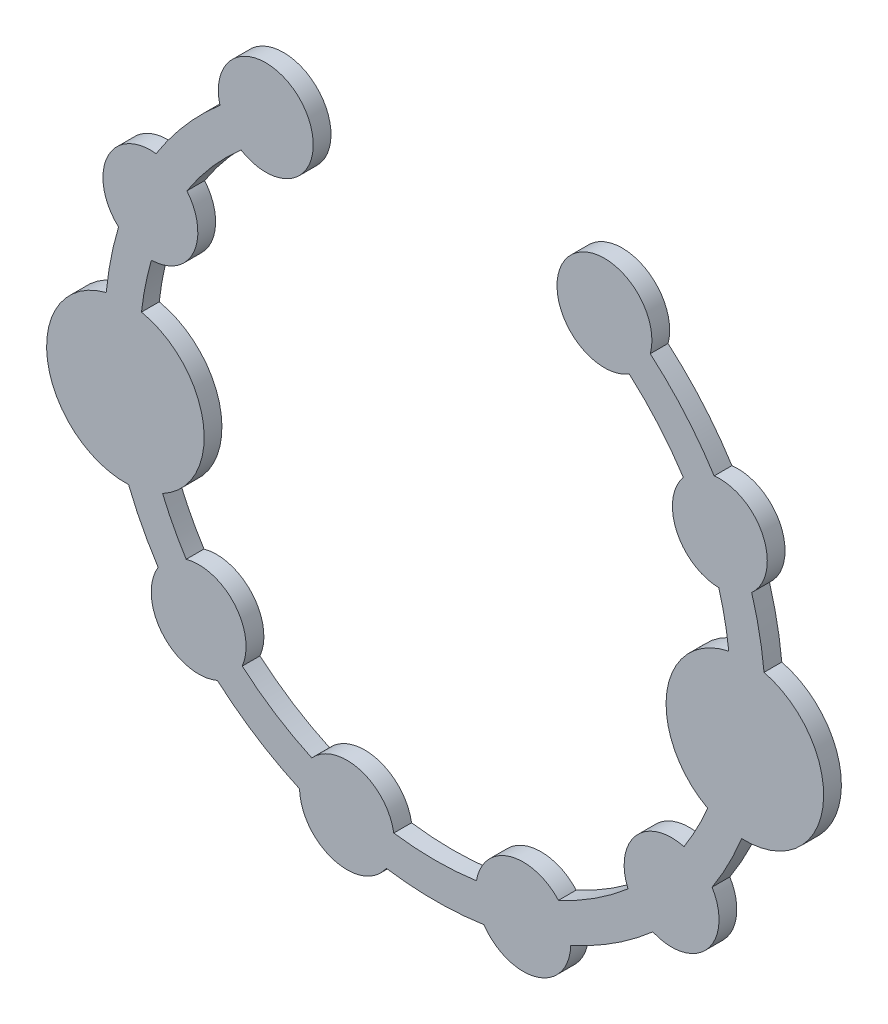
SolidWorks part; units mm, degrees
material "Copper"
ref_plane "Front Plane" through (0, 0, 0) normal (0, 0, 1) x (1, 0, 0)
ref_plane "Top Plane" through (0, 0, 0) normal (0, 1, 0) x (1, 0, 0)
ref_plane "Right Plane" through (0, 0, 0) normal (1, 0, 0) x (0, 0, -1)
sketch "Pads Sketch" plane through (0, 0, 0) normal (0, 0, 1) x (1, 0, 0)
  line L0 (0, 0) -> (0, -35.75) construction
  line L1 (0, 0) -> (-10.0698, -34.3025) construction
  line L2 (0, 0) -> (-10.0698, -34.3025) construction
  line L3 (0, 0) -> (-27.0136, -23.4164) construction
  line L4 (0, 0) -> (-35.3845, -5.099) construction
  circle A0 centre (0, 0) radius 35.75 construction
  circle A1 centre (-10.0698, -34.3025) radius 5.42
  circle A2 centre (-27.0136, -23.4164) radius 5.42
  circle A3 centre (-35.3845, -5.099) radius 5.42 [skipped]
  circle A4 centre (-32.5259, 14.8366) radius 5.42
  circle A5 centre (-19.3451, 30.0638) radius 5.42
  circle A6 centre (-35.3845, -5.099) radius 9
  dimension "D1" = 71.5
  dimension "D2" = 10.84
  dimension "D6" = 18
  dimension "D3" = 16.36
  dimension "D5" = 32.72
  dimension "D7" = 81.8
  dimension "D4" = 5
extrude "Pads" add sketch "Pads Sketch" along normal blind 2.03
sketch "Connector Sketch" plane through (0, 0, 2.03) normal (0, 0, 1) x (1, 0, 0)
  line L0 (0, 0) -> (0, -35.75) construction
  line L1 (0, -33.75) -> (0, -37.75)
  line L2 (-24.5782, 28.6527) -> (-22.176, 25.4418)
  arc A0 (0, -33.75) -> (-22.176, 25.4418) centre (0, 0) cw
  circle A1 centre (-19.3451, 30.0638) radius 5.42 construction
  arc A2 (0, -37.75) -> (-24.5782, 28.6527) centre (0, 0) cw
  dimension "D1" = 37.75
  dimension "D2" = 33.75
extrude "Connector" add sketch "Connector Sketch" against normal blind 2.03
mirror "Mirror Connector" about plane through (0, 0, 0) normal (1, 0, 0) of "Connector", "Pads"
mirror "Mirror Pads" about plane through (0, 0, 0) normal (1, 0, 0) of "Pads"
